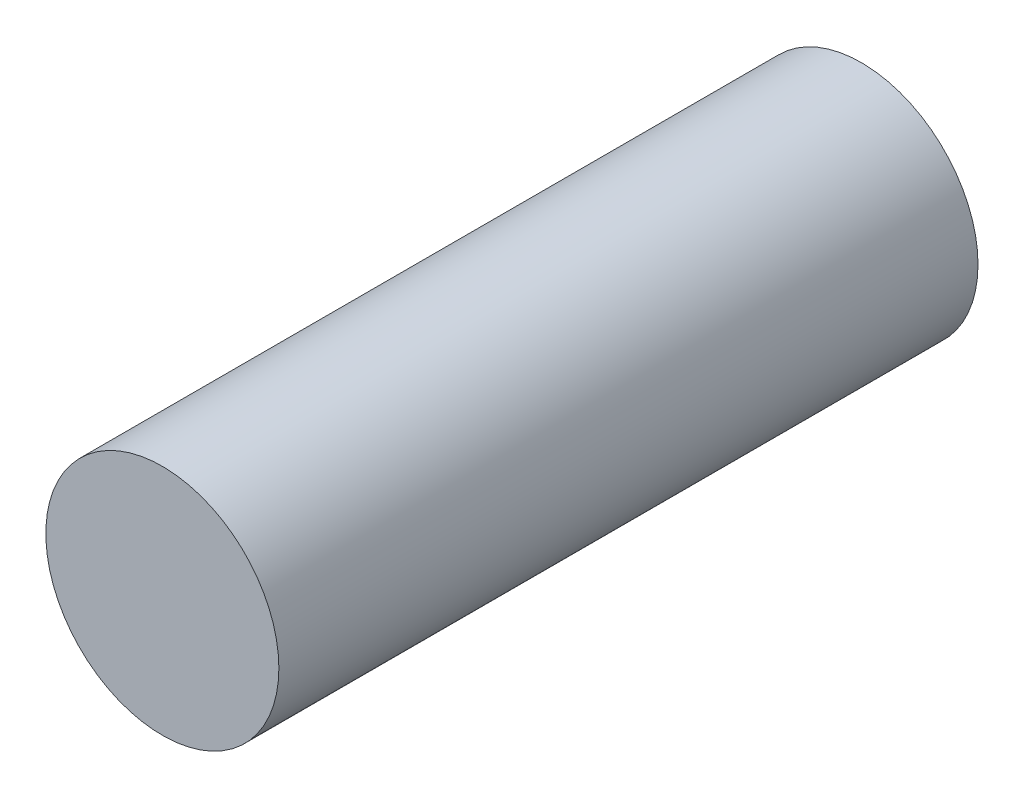
SolidWorks part; units mm, degrees
ref_plane "Přední rovina" through (0, 0, 0) normal (0, 0, 1) x (1, 0, 0)
ref_plane "Horní rovina" through (0, 0, 0) normal (0, 1, 0) x (1, 0, 0)
ref_plane "Pravá rovina" through (0, 0, 0) normal (1, 0, 0) x (0, 0, -1)
sketch "Sketch1" plane through (0, 0, 0) normal (0, 0, 1) x (1, 0, 0)
  circle A0 centre (0, 0) radius 5
  dimension "D1" = 10
extrude "Boss-Extrude1" add sketch "Sketch1" along normal blind 30 contours A0
